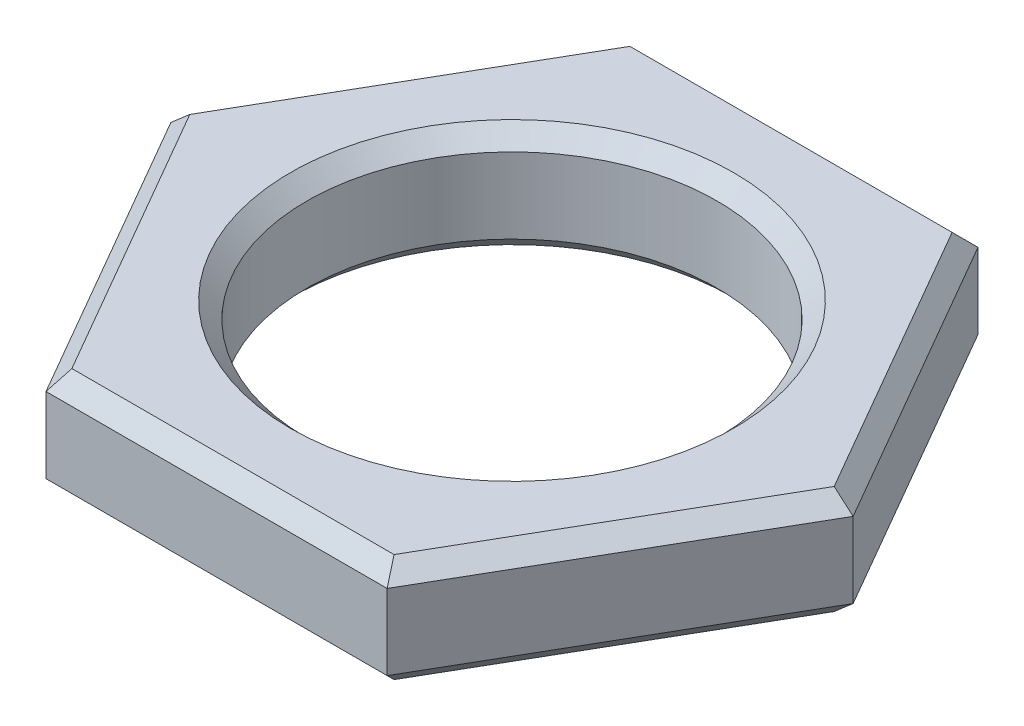
SolidWorks part; units mm, degrees
ref_plane "Front Plane" through (0, 0, 0) normal (0, 0, 1) x (1, 0, 0)
ref_plane "Top Plane" through (0, 0, 0) normal (0, 1, 0) x (1, 0, 0)
ref_plane "Right Plane" through (0, 0, 0) normal (1, 0, 0) x (0, 0, -1)
sketch "Sketch1" plane through (0, 0, 0) normal (0, 1, 0) x (1, 0, 0)
  line L1 (5.1962, 0) -> (2.5981, 4.5)
  line L2 (2.5981, 4.5) -> (-2.5981, 4.5)
  line L3 (-2.5981, 4.5) -> (-5.1962, 0)
  line L4 (-5.1962, 0) -> (-2.5981, -4.5)
  line L5 (-2.5981, -4.5) -> (2.5981, -4.5)
  line L6 (2.5981, -4.5) -> (5.1962, 0)
  circle A0 centre (0, 0) radius 4.5 construction
  circle A1 centre (0, 0) radius 3.125
  dimension "D2" = 6.25
  dimension "D1" = 9
extrude "Boss-Extrude1" add sketch "Sketch1" along normal blind 1.65
chamfer "Chamfer1" distance 0.25 angle 45
